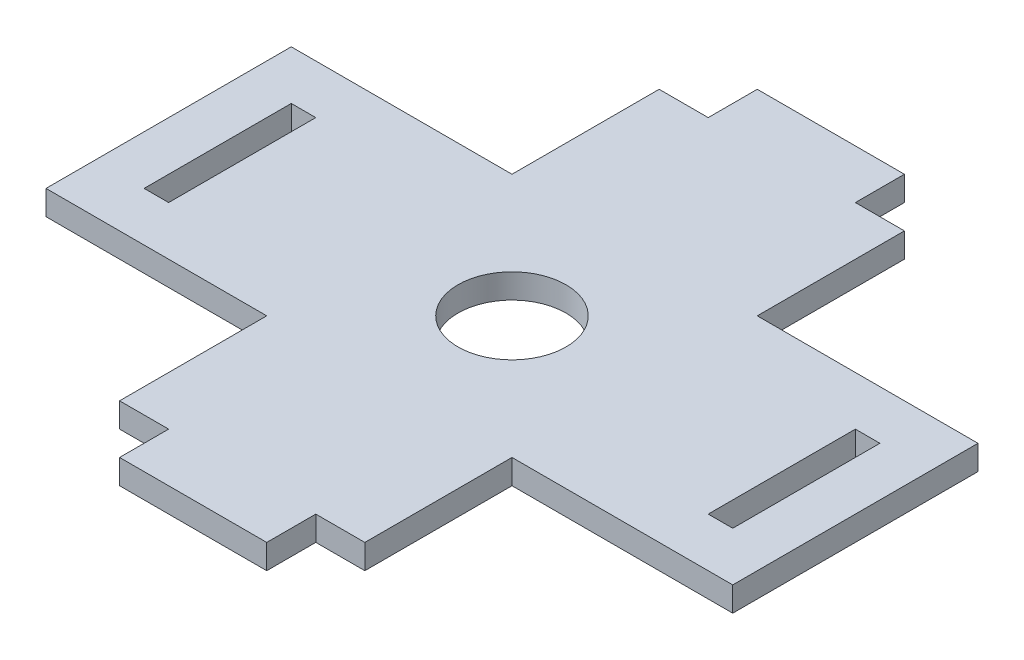
SolidWorks part; units mm, degrees
material "Acrylic (Medium-high impact)"
ref_plane "Front Plane" through (0, 0, 0) normal (0, 0, 1) x (1, 0, 0)
ref_plane "Top Plane" through (0, 0, 0) normal (0, 1, 0) x (1, 0, 0)
ref_plane "Right Plane" through (0, 0, 0) normal (1, 0, 0) x (0, 0, -1)
sketch "Sketch1" plane through (0, 0, 0) normal (0, 1, 0) x (1, 0, 0)
  line L0 (0, 55) -> (0, -55) construction
  line L1 (70, -55) -> (15, -55)
  line L2 (70, -55) -> (70, 55)
  line L3 (70, 55) -> (15, 55)
  line L4 (-70, -55) -> (-70, 55)
  line L5 (70, -55) -> (-70, 55) construction
  line L6 (70, 55) -> (-70, -55) construction
  line L7 (-15, 65) -> (15, 65)
  line L8 (-15, 65) -> (-15, 55)
  line L10 (15, 65) -> (15, 55)
  line L15 (0, 65) -> (0, 55) construction
  line L16 (-70, 0) -> (70, 0) construction
  line L18 (15, -65) -> (15, -55)
  line L19 (-15, -65) -> (15, -65)
  line L20 (-15, -65) -> (-15, -55)
  line L21 (-15, 55) -> (-70, 55)
  line L22 (-15, -55) -> (-70, -55)
  point P1 (0, 0)
  dimension "D1" = 140
  dimension "D2" = 110
  dimension "D3" = 30
  dimension "D4" = 10
extrude "Boss-Extrude2" add sketch "Sketch1" along normal blind 5
sketch "Sketch2" plane through (0, 5, 0) normal (0, 1, 0) x (1, 0, 0)
  line L0 (-60, 0) -> (-55, 0) construction
  line L1 (-60, 15) -> (-55, 15)
  line L2 (-60, 15) -> (-60, -15)
  line L3 (-60, -15) -> (-55, -15)
  line L4 (-55, 15) -> (-55, -15)
  line L5 (-70, 0) -> (70, 0) construction
  line L6 (-70, 55) -> (-70, -55) construction
  line L7 (70, -55) -> (70, 55) construction
  line L8 (0, 65) -> (0, -65) construction
  line L9 (15, 65) -> (-15, 65) construction
  line L10 (-15, -65) -> (15, -65) construction
  line L11 (60, -15) -> (55, -15)
  line L12 (55, 15) -> (55, -15)
  line L13 (60, 15) -> (55, 15)
  line L14 (60, 15) -> (60, -15)
  dimension "D1" = 5
  dimension "D2" = 30
  dimension "D3" = 10
extrude "Cut-Extrude4" cut sketch "Sketch2" against normal blind 100
sketch "Sketch3" plane through (0, 0, 0) normal (0, -1, 0) x (-1, 0, 0)
  circle A0 centre (0, 0) radius 11
  dimension "D1" = 22
extrude "Cut-Extrude5" cut sketch "Sketch3" against normal blind 100
sketch "Sketch5" plane through (0, 0, 0) normal (0, -1, 0) x (-1, 0, 0)
  line L0 (66.5014, 0) -> (-70, 0) construction
  line L1 (70, -55) -> (25, -55)
  line L2 (70, -55) -> (70, -25)
  line L3 (70, -25) -> (25, -25)
  line L4 (25, -55) -> (25, -25)
  line L5 (-70, -55) -> (-70, 55) construction
  line L6 (25, 55) -> (25, 25)
  line L7 (70, 25) -> (25, 25)
  line L8 (70, 55) -> (70, 25)
  line L9 (70, 55) -> (25, 55)
  line L10 (0, -65) -> (0, 65) construction
  line L11 (15, -65) -> (-15, -65) construction
  line L12 (-15, 65) -> (15, 65) construction
  line L13 (-70, 55) -> (-25, 55)
  line L14 (-70, 55) -> (-70, 25)
  line L15 (-70, 25) -> (-25, 25)
  line L16 (-25, 55) -> (-25, 25)
  line L17 (-25, -55) -> (-25, -25)
  line L18 (-70, -25) -> (-25, -25)
  line L19 (-70, -55) -> (-70, -25)
  line L20 (-70, -55) -> (-25, -55)
  dimension "D1" = 30
  dimension "D2" = 45
extrude "Cut-Extrude6" cut sketch "Sketch5" against normal blind 100
